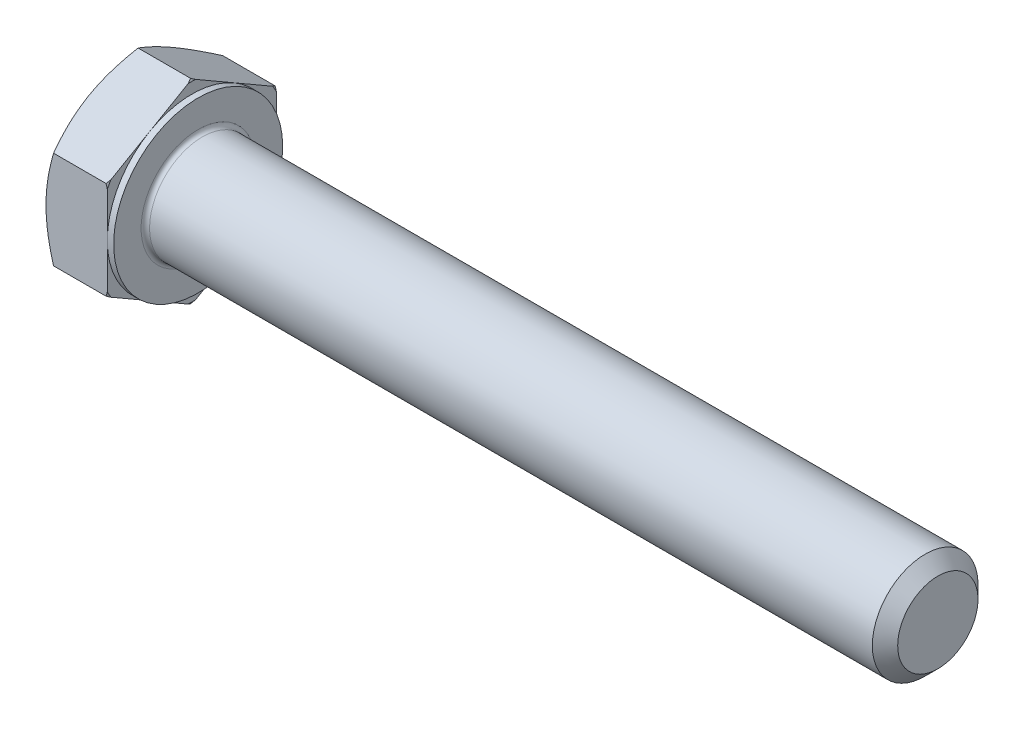
SolidWorks part; units mm, degrees
extrude "基体-拉伸" add sketch "草图1" along normal blind 6.4
sketch "草图1" plane through (0, 0, 0) normal (1, 0, 0) x (0, 0, -1)
  line L0 (8, 4.6188) -> (8, -4.6188)
  line L1 (-8, 4.6188) -> (-8, -4.6188)
  line L2 (8, -4.6188) -> (0, -9.2376)
  line L3 (0, -9.2376) -> (-8, -4.6188)
  line L4 (8, 4.6188) -> (0, 9.2376)
  line L5 (0, 9.2376) -> (-8, 4.6188)
  dimension "s" = 16
  dimension "D2" = 120
  dimension "D3" = 8
  dimension "D4" = 8
  dimension "D5" = 8
revolve "切除-旋转1" cut sketch "草图3" angle 360 about L6
sketch "草图3" plane through (0, 0, 0) normal (0, 0, 1) x (1, 0, 0)
  line L0 (0, 8) -> (3.6013, 14.2376)
  line L1 (0, 9.2376) -> (0, 4.6188) construction
  line L2 (3.6013, 14.2376) -> (3.6013, 19.2376)
  line L3 (3.6013, 19.2376) -> (-10, 19.2376)
  line L4 (-10, 19.2376) -> (-10, 8)
  line L5 (-10, 8) -> (0, 8)
  line L6 (0, 0) -> (99.06, 0) construction
  line L7 (6.4, 9.2376) -> (0, 9.2376) construction
  dimension "D1" = 8
  dimension "D2" = 5
  dimension "D3" = 10
  dimension "D4" = 5
  dimension "Head_ch_ang" = 30
material "3.6级"
ref_plane "前视" through (0, 0, 0) normal (0, 0, 1) x (1, 0, 0)
ref_plane "上视" through (0, 0, 0) normal (0, 1, 0) x (1, 0, 0)
ref_plane "右视" through (0, 0, 0) normal (1, 0, 0) x (0, 0, -1)
sketch "草图2" plane through (0, 0, 0) normal (0, 0, 1) x (1, 0, 0)
  line L0 (0, 4.6188) -> (0, -4.6188) construction
  line L1 (0, 0) -> (76.4, 0)
  line L2 (0, 0) -> (0, 5)
  line L3 (0, 5) -> (27.8072, 5)
  line L4 (76.4, 0) -> (76.4, 3.701)
  line L5 (6.4, 9.2376) -> (6.4, 4.6188) construction
  line L7 (0, 0) -> (96.52, 0) construction
  line L8 (76.4, -3.701) -> (27.8072, -5) construction
  line L9 (0, -5) -> (27.8072, -5) construction
  line L10 (7.9, 15.24) -> (7.9, -1.27) construction
  line L11 (50.4, 15.24) -> (50.4, -1.27) construction
  line L12 (6.4, 4.6188) -> (6.4, -4.6188) construction
  line L13 (27.8072, 5) -> (76.4, 5)
  line L14 (76.4, 5) -> (76.4, 3.701)
revolve "凸台-旋转1" add sketch "草图2" angle 360 about L7
cosmetic thread "螺旋线1" parameters "Thread_length"=26, "Thread_minor"=7.402
sketch "草图5" plane through (0, 0, 0) normal (0, 0, 1) x (1, 0, 0)
  line L0 (6.4, 8) -> (2.7987, 14.2376)
  line L1 (6.4, 9.2376) -> (6.4, 4.6188) construction
  line L2 (2.7987, 14.2376) -> (2.7987, 19.2376)
  line L3 (2.7987, 19.2376) -> (12.7987, 19.2376)
  line L4 (12.7987, 19.2376) -> (12.7987, 8)
  line L5 (12.7987, 8) -> (6.4, 8)
  line L7 (6.4, 9.2376) -> (0.7145, 9.2376) construction
  line L8 (0, 0) -> (99.06, 0) construction
  line L9 (0, 0) -> (99.06, 0) construction
  dimension "D1" = 8
  dimension "D2" = 5
  dimension "D3" = 10
  dimension "D4" = 5
  dimension "Head_ch_ang" = 30
revolve "切除-旋转2" cut sketch "草图5" angle 360 about L8
sketch "草图4" plane through (0, 0, 0) normal (0, 0, 1) x (1, 0, 0)
  line L1 (6.4, 9.2376) -> (6.4, 4.6188) construction
  line L2 (6.4, 8) -> (5.8, 8)
  line L3 (6.4, 8) -> (6.4, 19.2376)
  line L4 (6.4, 19.2376) -> (5.8, 19.2376)
  line L5 (0, 0) -> (95.25, 0) construction
  line L6 (0, 0) -> (96.52, 0) construction
  line L7 (5.8, 8) -> (5.8, 19.2376)
  line L8 (5.6855, 9.2376) -> (0.7145, 9.2376) construction
  dimension "D2" = 10
  dimension "D1" = 16
revolve "切除-旋转3" cut sketch "草图4" angle 360 about L5
chamfer "倒角" distance 1.2 angle 45 1 edges at (76.4, 0, 5)
fillet "圆角" radius 0.4 1 edges at (6.4, 0, -5)
sketch "草图6" plane through (0, 0, 0) normal (0, 0, 1) x (1, 0, 0)
  line L0 (50.4, -3.701) -> (49.65, -5)
  line L1 (50.4, -3.701) -> (51.15, -5)
  line L2 (51.15, -5) -> (51.15, -6.25)
  line L3 (-3.175, 0) -> (5.1513, 0) construction
  line L5 (51.15, -6.25) -> (49.65, -6.25)
  line L6 (49.65, -6.25) -> (49.65, -5)
  dimension "Thread_minor" = 7.402
  dimension "Diameter" = 10
  dimension "Start" = 50.4
revolve "切除-旋转4" [suppressed] cut sketch "草图6" angle 360 about L3
pattern_linear "阵列(线性)1" [suppressed]
equation "\"D3@草图1\" = \"s@草图1\" / 2"
equation "\"D4@草图1\" = \"D3@草图1\""
equation "\"D5@草图1\" = \"D4@草图1\""
equation "\"Thread_minor@螺旋线1\" = \"Minor_dia@草图2\""
equation "\"D1@草图3\" = \"s@草图1\" / 2"
equation "\"D1@草图5\" = \"s@草图1\" / 2"
equation "\"Head_ch_ang@草图5\" = \"Head_ch_ang@草图3\""
equation "\"D1@草图4\" = \"s@草图1\""
equation "\"Thread_length@螺旋线1\" = ((sgn( (\"l@草图2\" - \"p@草图2\" ) - \"h@草图2\" )-1)*( (\"l@草图2\" - \"p@草图2\" ) - \"h@草图2\" ))/-2+ \"h@草图2\""
equation "\"Thread_minor@草图6\" = \"Minor_dia@草图2\""
equation "\"Diameter@草图6\" = \"m@草图2\""
equation "\"Overcut@草图6\" = \"m@草图2\" * 1.25"
equation "\"Start@草图6\" = \"k@基体-拉伸\" + \"l@草图2\" - \"Thread_length@螺旋线1\"  '---Non-countersunk---"
equation "\"Num_threads@阵列(线性)1\" = int( \"Thread_length@螺旋线1\" / \"p@草图2\" + 0.999 )  + 1"
equation "\"Advance@阵列(线性)1\" = \"Thread_length@螺旋线1\" /  (\"Num_threads@阵列(线性)1\" - 1) 'relax it"
equation "\"Num_threads@阵列(线性)1\" = \"Num_threads@阵列(线性)1\" - sgn( \"Num_threads@阵列(线性)1\" - 1) '---chamfered tips only---"
equation "\"Minor_dia@草图2\" = \"m@草图2\"-\"p@草图2\" * 1.732"
equation "\"D1@倒角\" = \"p@草图2\"*0.8"
